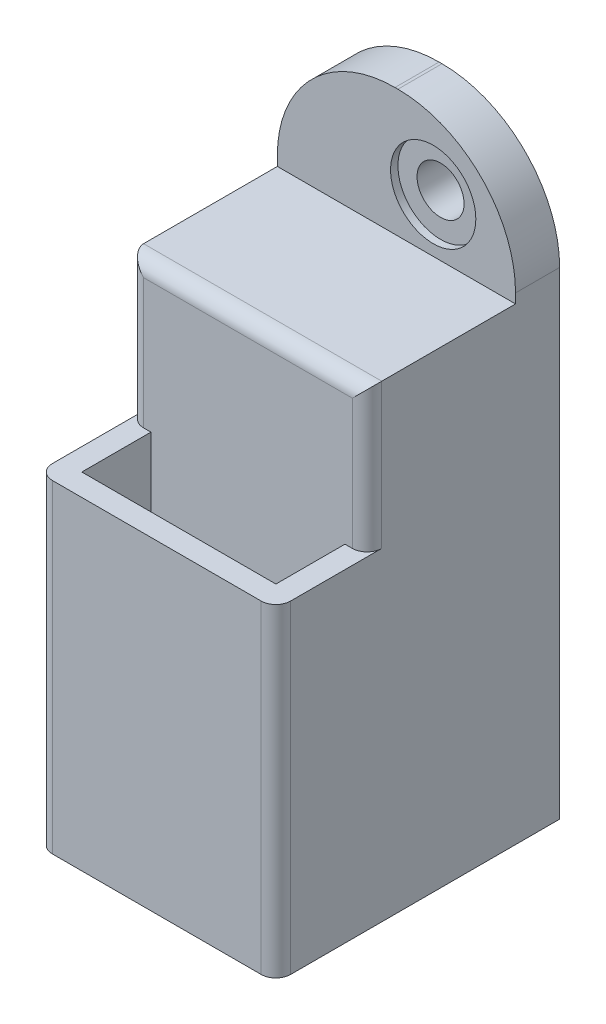
SolidWorks part; units mm, degrees
ref_plane "Alzado" through (0, 0, 0) normal (0, 0, 1) x (1, 0, 0)
ref_plane "Planta" through (0, 0, 0) normal (0, 1, 0) x (1, 0, 0)
ref_plane "Vista lateral" through (0, 0, 0) normal (1, 0, 0) x (0, 0, -1)
sketch "Croquis2" plane through (0, 0, 0) normal (0, 1, 0) x (1, 0, 0)
  line L0 (-1.5, 1.5) -> (14.7, 1.5)
  line L1 (0, 0) -> (13.2, 0)
  line L2 (0, 0) -> (0, -6.2)
  line L3 (0, -6.2) -> (13.2, -6.2)
  line L4 (13.2, 0) -> (13.2, -6.2)
  line L5 (14.7, 1.5) -> (14.7, -7.7)
  line L6 (-1.5, -7.7) -> (14.7, -7.7)
  line L7 (-1.5, 1.5) -> (-1.5, -7.7)
  dimension "D1" = 13.2
  dimension "D2" = 6.2
  dimension "D3" = 1.5
extrude "Saliente-Extruir1" add sketch "Croquis2" along normal blind 6.5
sketch "Croquis3" plane through (0, 0, -1.5) normal (0, 0, -1) x (-1, 0, 0)
  line L1 (1.5, 0) -> (-14.7, 0)
  line L2 (1.5, 0) -> (1.5, 12)
  line L3 (1.5, 12) -> (-14.7, 12)
  line L4 (-14.7, 0) -> (-14.7, 12)
  line L6 (-14.7, 0) -> (1.5, 0) construction
  line L8 (-14.7, 6.5) -> (-14.7, 0) construction
  line L9 (1.5, 6.5) -> (1.5, 0) construction
  dimension "D1" = 12
extrude "Saliente-Extruir2" add sketch "Croquis3" along normal blind 2
sketch "Croquis4" plane through (0, 0, -3.5) normal (0, 0, -1) x (-1, 0, 0)
  line L10 (1.5, 0) -> (1.5, 12) construction
  line L11 (1.5, 12) -> (-14.7, 12) construction
  line L12 (-14.7, 12) -> (-14.7, 0) construction
  line L13 (1.5, 0) -> (1.5, 12)
  line L14 (1.5, 12) -> (-14.7, 12)
  line L15 (-14.7, 12) -> (-14.7, 0)
  line L16 (-0.3, 0) -> (-0.3, 11)
  line L17 (-14.7, 0) -> (1.5, 0) construction
  line L18 (-0.3, 11) -> (-12.9, 11)
  line L19 (-12.9, 11) -> (-12.9, 0)
  line L20 (1.5, 0) -> (-0.3, 0)
  line L21 (-12.9, 0) -> (-14.7, 0)
  dimension "D1" = 1
  dimension "D2" = 1.8
  dimension "D3" = 1.8
extrude "Saliente-Extruir3" add sketch "Croquis4" along normal blind 8.1
sketch "Croquis5" plane through (0, 12, 0) normal (0, 1, 0) x (1, 0, 0)
  line L0 (-1.5, 11.6) -> (-1.5, 1.5) construction
  line L1 (14.7, 11.6) -> (-1.5, 11.6)
  line L2 (14.7, 11.6) -> (14.7, 8.6)
  line L3 (14.7, 8.6) -> (-1.5, 8.6)
  line L4 (-1.5, 11.6) -> (-1.5, 8.6)
  dimension "D1" = 3
extrude "Saliente-Extruir4" add sketch "Croquis5" along normal blind 13
sketch "Croquis6" plane through (0, 0, -8.6) normal (0, 0, 1) x (1, 0, 0)
  line L0 (14.7, 25) -> (14.7, 12) construction
  line L1 (-1.5, 25) -> (14.7, 25) construction
  circle A0 centre (9.1, 20) radius 1.6
  dimension "D1" = 3.2
  dimension "D2" = 5.6
  dimension "D3" = 5
extrude "Cortar-Extruir1" cut sketch "Croquis6" against normal up to surface (3 mm away) up to face at (6.6, 9, -11.6)
sketch "Croquis7" plane through (0, 0, -1.5) normal (0, 0, 1) x (1, 0, 0)
  line L0 (-1.5, 6.5) -> (-1.5, 12) construction
  line L1 (14.7, 6.5) -> (-1.5, 6.5)
  line L2 (14.7, 6.5) -> (14.7, 8.5)
  line L3 (14.7, 8.5) -> (-1.5, 8.5)
  line L4 (-1.5, 6.5) -> (-1.5, 8.5)
  dimension "D1" = 2
extrude "Saliente-Extruir5" add sketch "Croquis7" along normal blind 3
sketch "Croquis8" plane through (0, 0, -8.6) normal (0, 0, 1) x (1, 0, 0)
  circle A0 centre (9.1, 20) radius 2.9
  dimension "D1" = 5.8
extrude "Cortar-Extruir2" cut sketch "Croquis8" against normal blind 0.5
fillet "Redondeo1" radius 1 2 edges at (-1.5, 3.25, 7.7) (14.7, 3.25, 7.7)
fillet "Redondeo6" radius 8 2 edges at (14.7, 25, -10.1) (-1.5, 25, -10.1)
sketch "Croquis9" plane through (0, 0, 0) normal (0, -1, 0) x (1, 0, 0)
  line L0 (0, 0) -> (0, 6.2) construction
  line L1 (0, 6.2) -> (13.2, 6.2) construction
  line L2 (13.2, 6.2) -> (13.2, 0) construction
  line L3 (13.2, 0) -> (0, 0) construction
  line L4 (0, 0) -> (0, 6.2)
  line L5 (0, 6.2) -> (13.2, 6.2)
  line L6 (13.2, 6.2) -> (13.2, 0)
  line L7 (13.2, 0) -> (0, 0)
  line L8 (13.7, 7.7) -> (-0.5, 7.7)
  line L9 (-1.5, 6.7) -> (-1.5, -11.6)
  line L10 (-1.5, -11.6) -> (0.3, -11.6)
  line L11 (0.3, -11.6) -> (0.3, -3.5)
  line L12 (0.3, -3.5) -> (12.9, -3.5)
  line L13 (12.9, -3.5) -> (12.9, -11.6)
  line L14 (12.9, -11.6) -> (14.7, -11.6)
  line L15 (14.7, -11.6) -> (14.7, 6.7)
  line L16 (13.7, 7.7) -> (-0.5, 7.7)
  line L17 (-1.5, 6.7) -> (-1.5, -11.6)
  line L18 (-1.5, -11.6) -> (0.3, -11.6)
  line L19 (0.3, -11.6) -> (0.3, -3.5)
  line L20 (0.3, -3.5) -> (12.9, -3.5)
  line L21 (12.9, -3.5) -> (12.9, -11.6)
  line L22 (12.9, -11.6) -> (14.7, -11.6)
  line L23 (14.7, -11.6) -> (14.7, 6.7)
  arc A2 (-0.5, 7.7) -> (-1.5, 6.7) centre (-0.5, 6.7) ccw
  arc A3 (14.7, 6.7) -> (13.7, 7.7) centre (13.7, 6.7) ccw
  arc A4 (-0.5, 7.7) -> (-1.5, 6.7) centre (-0.5, 6.7) ccw
  arc A5 (14.7, 6.7) -> (13.7, 7.7) centre (13.7, 6.7) ccw
  dimension "D1" = 0
extrude "Saliente-Extruir6" add sketch "Croquis9" along normal blind 3.5
sketch "Croquis10" plane through (0, 6.5, 0) normal (0, -1, 0) x (1, 0, 0)
  line L4 (0, 1.5) -> (0, 0)
  line L5 (0, 0) -> (13.2, 0)
  line L6 (13.2, 0) -> (13.2, 1.5)
  line L7 (13.2, 1.5) -> (0, 1.5)
  line L8 (0, 1.5) -> (0, 0)
  line L9 (0, 0) -> (13.2, 0)
  line L10 (13.2, 0) -> (13.2, 1.5)
  line L11 (13.2, 1.5) -> (0, 1.5)
  dimension "D1" = 0
extrude "Saliente-Extruir7" add sketch "Croquis10" along normal blind 3.5
sketch "Croquis11" plane through (0, -3.5, 0) normal (0, -1, 0) x (1, 0, 0)
  line L0 (0, 6.2) -> (0, 0) construction
  line L1 (13.2, 6.2) -> (0, 6.2) construction
  line L2 (13.2, 0) -> (13.2, 6.2) construction
  line L3 (0, 0) -> (13.2, 0) construction
  line L4 (0, 6.2) -> (0, 0)
  line L5 (13.2, 6.2) -> (0, 6.2)
  line L6 (13.2, 0) -> (13.2, 6.2)
  line L7 (0, 0) -> (13.2, 0)
  line L8 (13.7, 7.7) -> (-0.5, 7.7)
  line L9 (-1.5, 6.7) -> (-1.5, -11.6)
  line L10 (-1.5, -11.6) -> (0.3, -11.6)
  line L11 (0.3, -11.6) -> (0.3, -3.5)
  line L12 (0.3, -3.5) -> (12.9, -3.5)
  line L13 (12.9, -3.5) -> (12.9, -11.6)
  line L14 (12.9, -11.6) -> (14.7, -11.6)
  line L15 (14.7, -11.6) -> (14.7, 6.7)
  line L16 (13.7, 7.7) -> (-0.5, 7.7)
  line L17 (-1.5, 6.7) -> (-1.5, -11.6)
  line L18 (-1.5, -11.6) -> (0.3, -11.6)
  line L19 (0.3, -11.6) -> (0.3, -3.5)
  line L20 (0.3, -3.5) -> (12.9, -3.5)
  line L21 (12.9, -3.5) -> (12.9, -11.6)
  line L22 (12.9, -11.6) -> (14.7, -11.6)
  line L23 (14.7, -11.6) -> (14.7, 6.7)
  arc A2 (14.7, 6.7) -> (13.7, 7.7) centre (13.7, 6.7) ccw
  arc A3 (-0.5, 7.7) -> (-1.5, 6.7) centre (-0.5, 6.7) ccw
  arc A4 (14.7, 6.7) -> (13.7, 7.7) centre (13.7, 6.7) ccw
  arc A5 (-0.5, 7.7) -> (-1.5, 6.7) centre (-0.5, 6.7) ccw
  dimension "D1" = 0
extrude "Saliente-Extruir8" add sketch "Croquis11" along normal blind 12
sketch "Croquis12" plane through (0, 3, 0) normal (0, -1, 0) x (1, 0, 0)
  line L4 (13.2, 1.5) -> (0, 1.5)
  line L5 (0, 1.5) -> (0, 0)
  line L6 (0, 0) -> (13.2, 0)
  line L7 (13.2, 0) -> (13.2, 1.5)
  line L8 (13.2, 1.5) -> (0, 1.5)
  line L9 (0, 1.5) -> (0, 0)
  line L10 (0, 0) -> (13.2, 0)
  line L11 (13.2, 0) -> (13.2, 1.5)
  dimension "D1" = 0
extrude "Saliente-Extruir9" add sketch "Croquis12" along normal blind 12
sketch "Croquis13" plane through (0, 0, -8.6) normal (0, 0, 1) x (1, 0, 0)
  line L0 (14.7, 17) -> (14.7, 12) construction
  line L1 (14.7, 16.35) -> (-1.5, 16.35)
  line L2 (14.7, 16.35) -> (14.7, 8.5)
  line L3 (14.7, 8.5) -> (-1.5, 8.5)
  line L4 (-1.5, 16.35) -> (-1.5, 8.5)
  line L5 (-1.5, 17) -> (-1.5, 12) construction
  line L6 (14.7, 8.5) -> (-1.5, 8.5) construction
  line L7 (14.7, 8.5) -> (-1.5, 8.5) construction
  line L8 (-1.5, 12) -> (14.7, 12) construction
  dimension "D1" = 4.35
extrude "Saliente-Extruir10" add sketch "Croquis13" along normal up to surface (10.1 mm away) up to face at (6.6, 3.125, 1.5)
sketch "Croquis14" plane through (0, 0, -11.6) normal (0, 0, -1) x (-1, 0, 0)
  line L0 (-0.3, 11) -> (-0.3, 8.5) construction
  line L1 (-12.9, 8.5) -> (-0.3, 8.5)
  line L2 (-12.9, 8.5) -> (-12.9, 15)
  line L3 (-12.9, 15) -> (-0.3, 15)
  line L4 (-0.3, 8.5) -> (-0.3, 15)
  dimension "D1" = 6.5
extrude "Cortar-Extruir3" cut sketch "Croquis14" against normal up to surface (8.1 mm away) up to face at (6.6, -3.5, -3.5)
fillet "Redondeo7" radius 1 3 edges at (6.6, 16.35, 1.5) (-1.5, 11.425, 1.5) (14.7, 11.425, 1.5)
